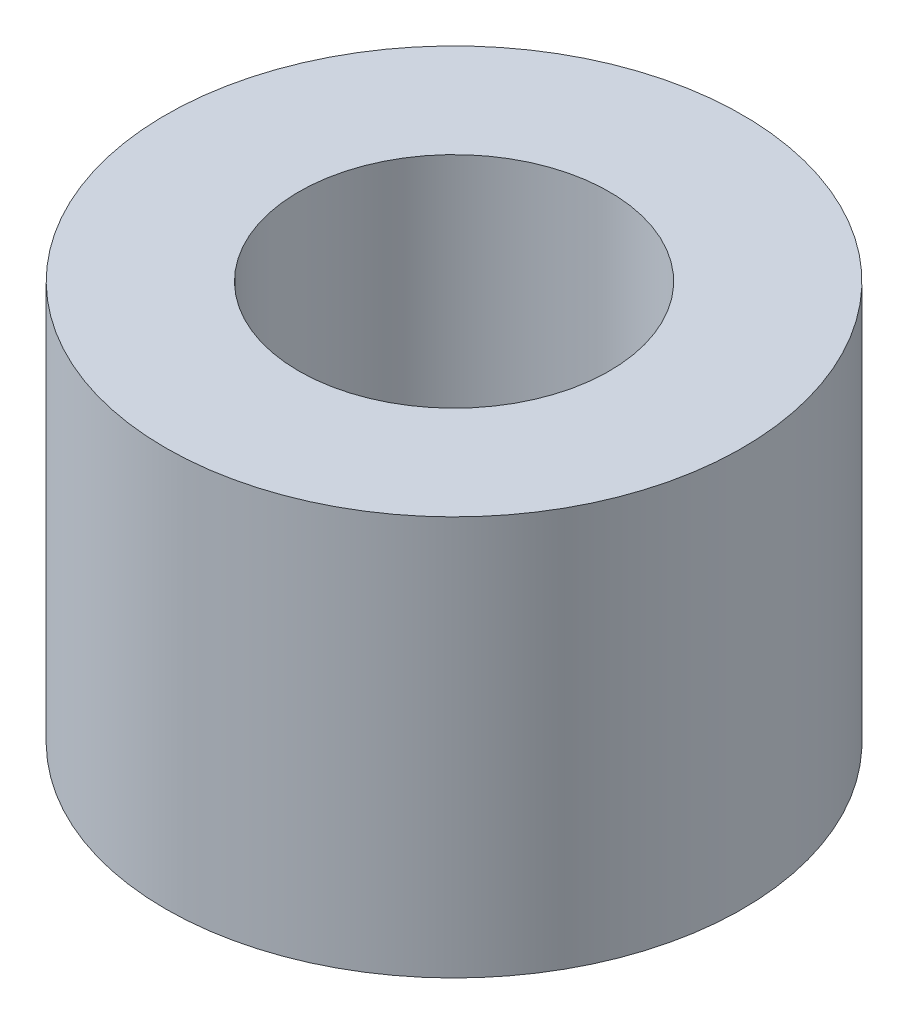
SolidWorks part; units mm, degrees
other "标注1"
sketch "草图3" plane through (0, 5, 29.5) normal (-0.6417, 0.7662, 0.0339) x (0.7661, 0.6384, 0.0747)
ref_plane "前视基准面" through (0, 0, 0) normal (0, 0, 1) x (1, 0, 0)
ref_plane "上视基准面" through (0, 0, 0) normal (0, 1, 0) x (1, 0, 0)
ref_plane "右视基准面" through (0, 0, 0) normal (1, 0, 0) x (0, 0, -1)
other "Configuration Table"
sketch "草图1" plane through (0, 0, 0) normal (0, 1, 0) x (1, 0, 0)
  circle A16 centre (0, 0) radius 3.25
  circle A17 centre (0, 0) radius 1.75
  point P0 (-90.6464, 22.0667)
  dimension "D1" = 3.5
  dimension "D2" = 1.5
extrude "凸台-拉伸1" add sketch "草图1" along normal blind 4.5
